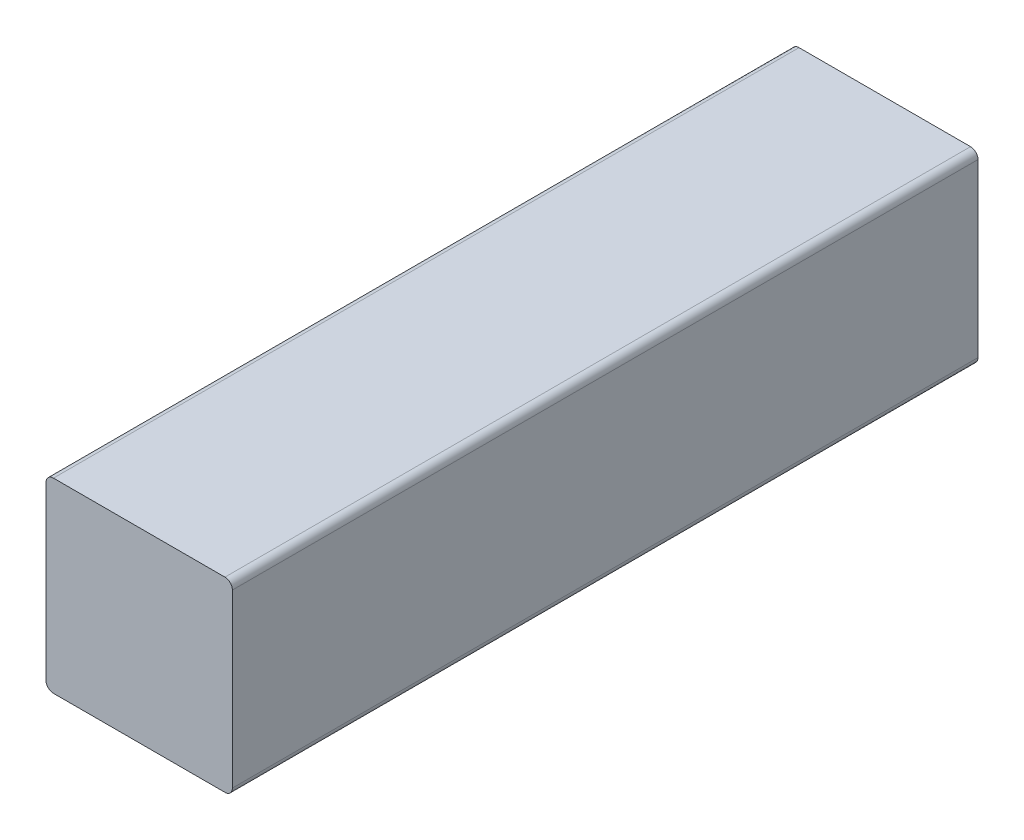
SolidWorks part; units mm, degrees
material "6061 Alloy"
ref_plane "Front Plane" through (0, 0, 0) normal (0, 0, 1) x (1, 0, 0)
ref_plane "Top Plane" through (0, 0, 0) normal (0, 1, 0) x (1, 0, 0)
ref_plane "Right Plane" through (0, 0, 0) normal (1, 0, 0) x (0, 0, -1)
sketch "Sketch1" plane through (0, 0, 0) normal (0, 0, 1) x (1, 0, 0)
  line L1 (0, 0) -> (6.35, 0)
  line L2 (0, 0) -> (0, 6.35)
  line L3 (0, 6.35) -> (6.35, 6.35)
  line L4 (6.35, 0) -> (6.35, 6.35)
  dimension "D1" = 6.35
extrude "Boss-Extrude1" add sketch "Sketch1" against normal blind 25.4
fillet "Fillet1" radius 0.254 4 edges at (6.35, 6.35, -12.7) (0, 6.35, -12.7) (0, 0, -12.7) (6.35, 0, -12.7)
